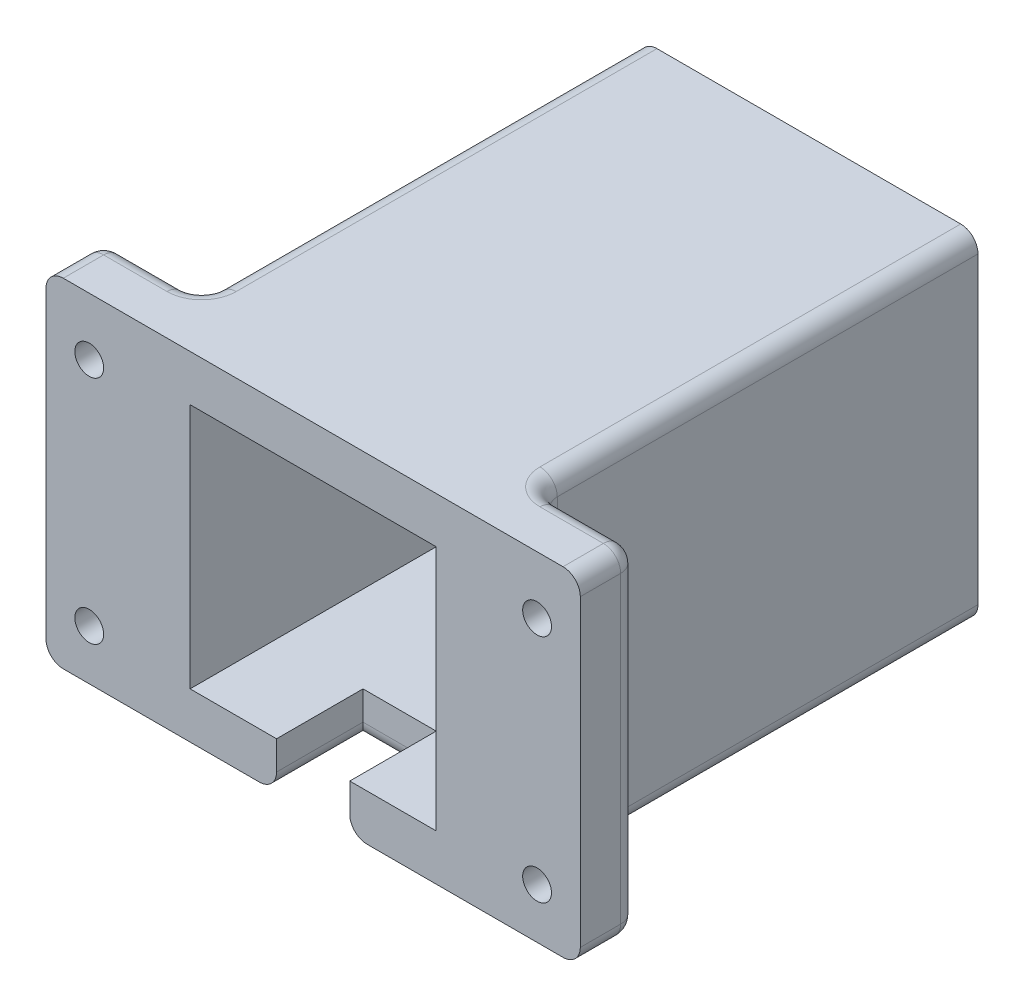
SolidWorks part; units mm, degrees
ref_plane "Alzado" through (0, 0, 0) normal (0, 0, 1) x (1, 0, 0)
ref_plane "Planta" through (0, 0, 0) normal (0, 1, 0) x (1, 0, 0)
ref_plane "Vista lateral" through (0, 0, 0) normal (1, 0, 0) x (0, 0, -1)
sketch "Croquis1" plane through (0, 0, 0) normal (0, 0, 1) x (1, 0, 0)
  line L0 (0, 8) -> (0, 0)
  line L1 (0, 0) -> (58.7, 0)
  line L3 (0, 8) -> (58.7, 8)
  line L5 (8, 8) -> (50.7, 8)
  line L9 (0, 8) -> (58.7, 8)
  line L10 (0, 8) -> (0, 58.7)
  line L11 (0, 58.7) -> (58.7, 58.7)
  line L12 (58.7, 8) -> (58.7, 58.7)
  line L13 (58.7, 8) -> (58.7, 0)
  point P0 (0, 0)
  dimension "D1" = 58.7
  dimension "D2" = 58.7
  dimension "D4" = 50.7
extrude "Saliente-Extruir1" add sketch "Croquis1" against normal blind 86
sketch "Croquis2" plane through (0, 0, 0) normal (0, 0, 1) x (1, 0, 0)
  line L1 (8, 50.7) -> (50.7, 50.7)
  line L2 (8, 50.7) -> (8, 8)
  line L3 (8, 8) -> (50.7, 8)
  line L4 (50.7, 50.7) -> (50.7, 8)
  line L5 (0, 0) -> (0, 58.7) construction
  line L6 (0, 58.7) -> (58.7, 58.7) construction
  line L7 (58.7, 0) -> (58.7, 58.7) construction
  line L8 (0, 0) -> (58.7, 0) construction
  dimension "D1" = 8
  dimension "D2" = 8
  dimension "D3" = 8
  dimension "D4" = 8
extrude "Cortar-Extruir1" cut sketch "Croquis2" against normal blind 53
sketch "Croquis3" plane through (0, 0, -53) normal (0, 0, 1) x (1, 0, 0)
  line L0 (8, 50.7) -> (8, 8) construction
  line L1 (50.7, 50.7) -> (8, 50.7) construction
  circle A0 centre (29.35, 29.35) radius 18.5
  dimension "D1" = 37
  dimension "D2" = 21.35
  dimension "D3" = 21.35
extrude "Cortar-Extruir2" cut sketch "Croquis3" against normal blind 30
sketch "Croquis4" plane through (0, 0, -83) normal (0, 0, 1) x (1, 0, 0)
  circle A0 centre (29.35, 29.35) radius 11.5
  dimension "D1" = 23
extrude "Cortar-Extruir3" cut sketch "Croquis4" against normal through all
sketch "Croquis5" plane through (0, 0, -83) normal (0, 0, 1) x (1, 0, 0)
  line L1 (29.35, 29.35) -> (29.35, 43.35)
  line L2 (29.35, 29.35) -> (39.2495, 39.2495)
  circle A0 centre (29.35, 29.35) radius 14
  circle A3 centre (39.2495, 39.2495) radius 1.5
  dimension "D1" = 28
  dimension "D3" = 3
  dimension "D2" = 45
extrude "Cortar-Extruir4" cut sketch "Croquis5" against normal through all contours A0 A3 L2 | A0 A3 | L2 A3 A0
pattern_circular "MatrizC1" count 4 over 360 about axis through (29.35, 29.35, 0) along (0, 0, 1) of "Cortar-Extruir4"
sketch "Croquis6" plane through (0, 0, -86) normal (0, 0, -1) x (-1, 0, 0)
  line L1 (-29.35, 0) -> (-29.35, 58.7)
  line L2 (0, 58.7) -> (-58.7, 58.7) construction
  line L3 (0, 0) -> (-58.7, 0) construction
  circle A0 centre (-29.35, 45.6) radius 1
  circle A1 centre (-29.35, 13.1) radius 1
  circle A2 centre (-29.35, 29.35) radius 11.5 construction
  circle A3 centre (-29.35, 52.35) radius 1
  circle A4 centre (-29.35, 6.35) radius 1
  dimension "D1" = 2
  dimension "D4" = 2
  dimension "2" = 2
  dimension "D6" = 2
  dimension "D2" = 32.5
  dimension "D3" = 16.25
  dimension "D7" = 46
  dimension "D8" = 23
extrude "Cortar-Extruir5" cut sketch "Croquis6" against normal blind 5 contours L1 A3 | L1 A3 | L1 A0 | L1 A0 | L1 A1 | L1 A1 | L1 A4 | L1 A4
sketch "Croquis7" plane through (0, 0, 0) normal (0, 0, 1) x (1, 0, 0)
  line L1 (8, 50.7) -> (50.7, 50.7)
  line L2 (8, 50.7) -> (8, 8)
  line L3 (8, 8) -> (50.7, 8)
  line L4 (50.7, 50.7) -> (50.7, 8)
  line L5 (-17.0027, 58.7) -> (75.7, 58.7)
  line L6 (-17.0027, 58.7) -> (-17.0027, 0)
  line L7 (-17.0027, 0) -> (75.7, 0)
  line L8 (75.7, 58.7) -> (75.7, 0)
  line L9 (0, 58.7) -> (58.7, 58.7) construction
  line L13 (0, 0) -> (58.7, 0) construction
  circle A0 centre (-9.5027, 48.7) radius 2.5
  circle A1 centre (68.2, 48.7) radius 2.5
  circle A2 centre (-9.5027, 8.7) radius 2.5
  circle A3 centre (68.2, 8.7) radius 2.5
  point P15 (8, 50.7)
  point P20 (50.7, 8)
  point P22 (85.6108, -1.9108)
  point P25 (8, 8)
  point P27 (-17.0027, 8)
  point P28 (-17.0027, -3.9305)
  point P29 (-17.0027, -1.3445)
  dimension "D5" = 5
  dimension "D8" = 5
  dimension "D2" = 40
  dimension "D3" = 25.0027
  dimension "D4" = 25
  dimension "D6" = 10
  dimension "D7" = 7.5
  dimension "D9" = 7.5
  dimension "D10" = 10
  dimension "D11" = 2
extrude "Saliente-Extruir2" add sketch "Croquis7" against normal blind 10
sketch "Croquis9" plane through (0, 0, 0) normal (0, 0, 1) x (1, 0, 0)
  line L1 (23, 8) -> (35.7, 8)
  line L2 (23, 8) -> (23, 0)
  line L3 (23, 0) -> (35.7, 0)
  line L4 (35.7, 8) -> (35.7, 0)
  line L5 (-17.0027, 0) -> (75.7, 0) construction
  line L8 (8, 50.7) -> (8, 8) construction
  line L9 (50.7, 8) -> (50.7, 50.7) construction
  line L10 (8, 8) -> (50.7, 8) construction
  dimension "D1" = 15
  dimension "D2" = 15
extrude "Cortar-Extruir7" cut sketch "Croquis9" against normal blind 15
fillet "Redondeo1" radius 3 19 edges at (58.7, 58.7, -48) (23, 0, -7.5) (29.35, 0, -15) (35.7, 0, -7.5) (0, 29.35, -10) (0, 58.7, -48) (67.2, 58.7, -10) (75.7, 58.7, -5) (75.7, 0, -5) (58.7, 29.35, -10) (0, 0, -48) (58.7, 0, -48) (-17.0027, 0, -5) (-17.0027, 58.7, -5) (-8.5013, 58.7, -10) (-17.0027, 29.35, -10) (-8.5013, 0, -10) (67.2, 0, -10) (75.7, 29.35, -10)
sketch "Croquis10" plane through (0, 0, -86) normal (0, 0, -1) x (-1, 0, 0)
  line L0 (-44.85, 13.85) -> (-13.85, 13.85)
  line L1 (-44.85, 13.85) -> (-44.85, 44.85)
  line L2 (-44.85, 44.85) -> (-13.85, 44.85)
  line L3 (-13.85, 13.85) -> (-13.85, 44.85)
  circle A0 centre (-44.85, 44.85) radius 3
  circle A1 centre (-13.85, 44.85) radius 3
  circle A2 centre (-13.85, 13.85) radius 3
  circle A3 centre (-44.85, 13.85) radius 3
  circle A4 centre (-29.35, 29.35) radius 11.5 construction
  dimension "D3" = 6
  dimension "D4" = 6
  dimension "D5" = 6
  dimension "D6" = 6
  dimension "D7" = 15.5
  dimension "D1" = 31
  dimension "D2" = 31
  dimension "D8" = 15.5
extrude "Cortar-Extruir8" cut sketch "Croquis10" against normal blind 29 contours L2 A0 L1 | L1 A0 L2 | L2 A1 L3 | L3 A1 L2 | L3 A2 L0 | L0 A2 L3 | L1 A3 L0 | L0 A3 L1
sketch "Croquis11" plane through (0, 0, -57) normal (0, 0, -1) x (-1, 0, 0)
  circle A0 centre (-44.85, 44.85) radius 1.5
  circle A1 centre (-13.85, 44.85) radius 1.5
  circle A2 centre (-13.85, 13.85) radius 1.5
  circle A3 centre (-44.85, 13.85) radius 1.5
  dimension "D1" = 3
  dimension "D2" = 3
  dimension "D3" = 3
  dimension "D4" = 3
extrude "Cortar-Extruir9" cut sketch "Croquis11" against normal blind 4
